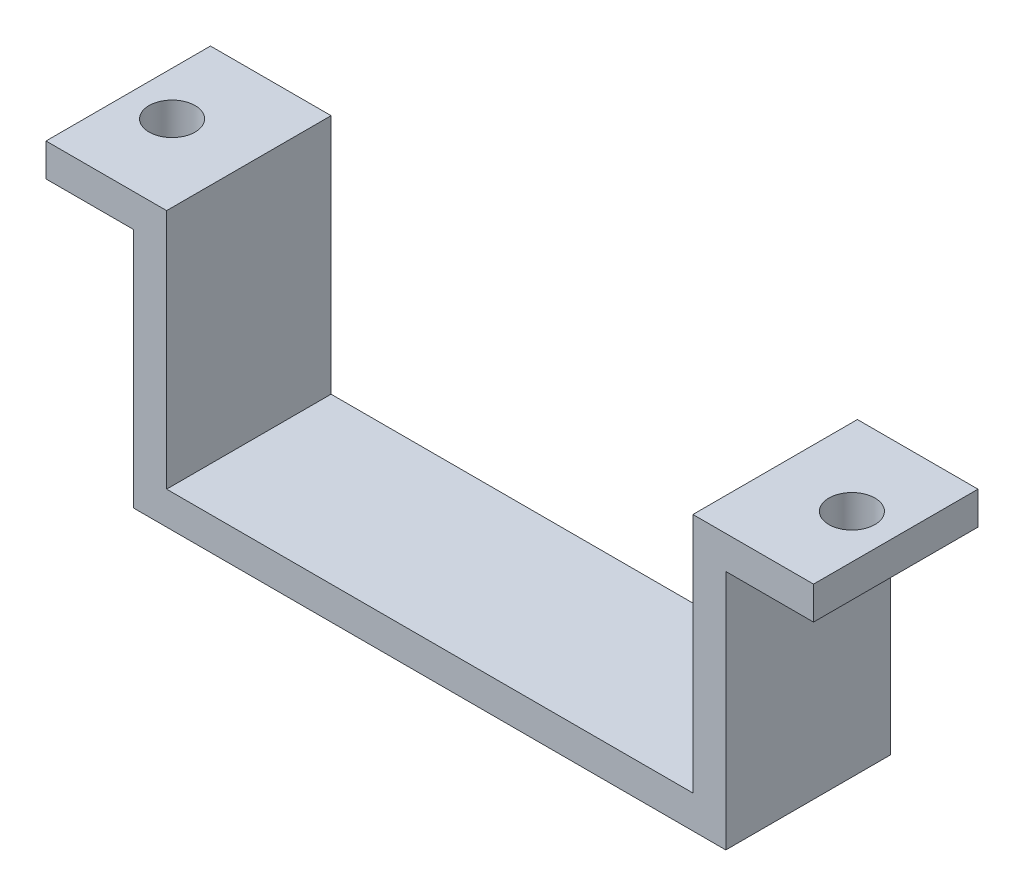
SolidWorks part; units mm, degrees
ref_plane "前视基准面" through (0, 0, 0) normal (0, 0, 1) x (1, 0, 0)
ref_plane "上视基准面" through (0, 0, 0) normal (0, 1, 0) x (1, 0, 0)
ref_plane "右视基准面" through (0, 0, 0) normal (1, 0, 0) x (0, 0, -1)
sketch "草图1" plane through (0, 0, 0) normal (0, 1, 0) x (1, 0, 0)
  line L1 (-24, 7.5) -> (24, 7.5)
  line L2 (-24, 7.5) -> (-24, -7.5)
  line L3 (-24, -7.5) -> (24, -7.5)
  line L4 (24, 7.5) -> (24, -7.5)
  dimension "D1" = 48
  dimension "D2" = 15
  dimension "D3" = 24
  dimension "D4" = 7.5
extrude "凸台-拉伸1" add sketch "草图1" along normal blind 3
sketch "草图2" plane through (0, 0, 0) normal (0, 1, 0) x (1, 0, 0)
  line L0 (0, 7.5) -> (0, -7.5) construction
  line L1 (24, 7.5) -> (27, 7.5)
  line L2 (24, 7.5) -> (24, -7.5)
  line L3 (24, -7.5) -> (27, -7.5)
  line L4 (27, 7.5) -> (27, -7.5)
  line L5 (24, 7.5) -> (-24, 7.5) construction
  line L6 (-24, -7.5) -> (24, -7.5) construction
  line L7 (-24, -7.5) -> (-27, -7.5)
  line L8 (-27, 7.5) -> (-27, -7.5)
  line L9 (-24, 7.5) -> (-27, 7.5)
  line L10 (-24, 7.5) -> (-24, -7.5)
  dimension "D1" = 3
  dimension "D2" = 15
extrude "凸台-拉伸2" add sketch "草图2" along normal blind 25
sketch "草图3" plane through (27, 0, 0) normal (1, 0, 0) x (0, 0, -1)
  line L0 (7.5, 25) -> (7.5, 0) construction
  line L1 (7.5, 22) -> (-7.5, 22)
  line L2 (7.5, 22) -> (7.5, 25)
  line L3 (7.5, 25) -> (-7.5, 25)
  line L4 (-7.5, 22) -> (-7.5, 25)
  dimension "D1" = 3
extrude "凸台-拉伸3" add sketch "草图3" along normal blind 8
mirror "镜向1" about plane through (0, 0, 0) normal (1, 0, 0) of "凸台-拉伸3"
sketch "草图4" plane through (0, 0, 0) normal (0, 1, 0) x (1, 0, 0)
  circle A0 centre (-31, 0) radius 2.1
  dimension "D1" = 4.2
  dimension "D2" = 31
extrude "切除-拉伸3" cut sketch "草图4" along normal blind 100
mirror "镜向2" about plane through (0, 0, 0) normal (1, 0, 0) of "切除-拉伸3"
